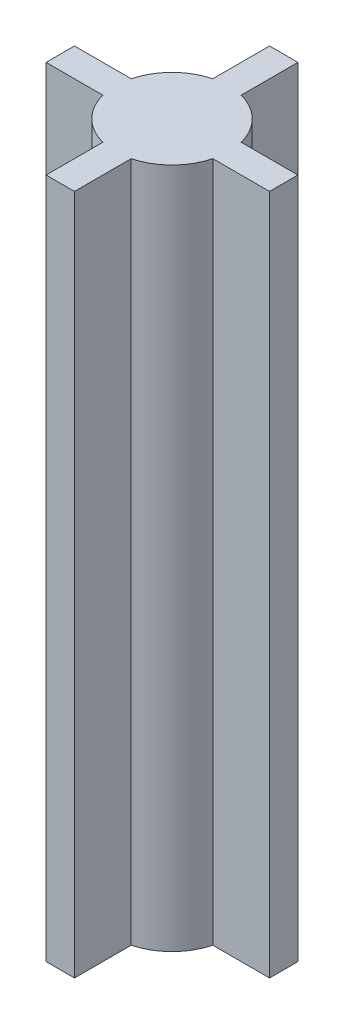
SolidWorks part; units mm, degrees
ref_plane "Front Plane" through (0, 0, 0) normal (0, 0, 1) x (1, 0, 0)
ref_plane "Top Plane" through (0, 0, 0) normal (0, 1, 0) x (1, 0, 0)
ref_plane "Right Plane" through (0, 0, 0) normal (1, 0, 0) x (0, 0, -1)
sketch "Sketch1" plane through (0, 0, 0) normal (0, 1, 0) x (1, 0, 0)
  line L0 (-3.175, 12.2967) -> (3.175, 12.2967)
  line L1 (-3.175, 12.2967) -> (-3.175, 24.9967)
  line L2 (3.175, 12.2967) -> (3.175, 24.9967)
  line L3 (-3.175, 24.9967) -> (3.175, 24.9967)
  line L4 (12.2967, 3.175) -> (24.9967, 3.175)
  line L5 (24.9967, 3.175) -> (24.9967, -3.175)
  line L6 (12.2967, -3.175) -> (24.9967, -3.175)
  line L7 (3.175, -12.2967) -> (3.175, -24.9967)
  line L8 (3.175, -24.9967) -> (-3.175, -24.9967)
  line L9 (-3.175, -12.2967) -> (-3.175, -24.9967)
  line L10 (-12.2967, -3.175) -> (-24.9967, -3.175)
  line L11 (-24.9967, -3.175) -> (-24.9967, 3.175)
  line L12 (-12.2967, 3.175) -> (-24.9967, 3.175)
  circle A0 centre (0, 0) radius 12.7
  point P3 (0, 12.2967)
  point P23 (0, 0)
  dimension "D1" = 25.4
  dimension "D2" = 12.7
  dimension "D3" = 6.35
  dimension "D4" = 4
extrude "Boss-Extrude1" add sketch "Sketch1" along normal blind 152.4 contours A0 L0 | A0 L12 L11 L10 | A0 L9 L8 L7 | A0 L6 L5 L4 | A0 L2 L3 L1 | L0 A0
